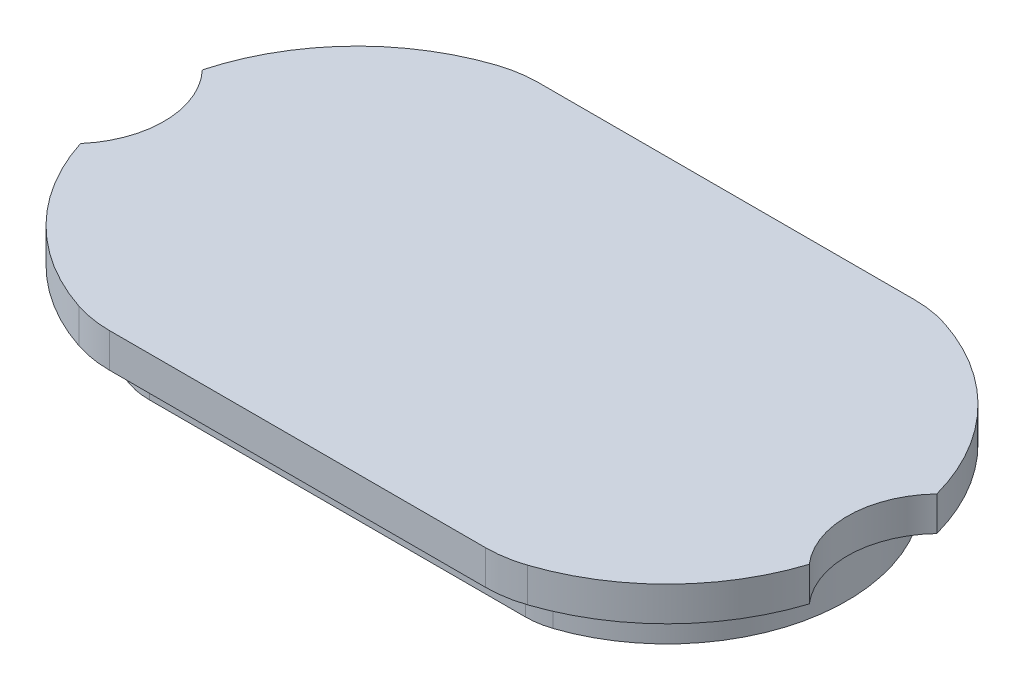
SolidWorks part; units mm, degrees
ref_plane "Front Plane" through (0, 0, 0) normal (0, 0, 1) x (1, 0, 0)
ref_plane "Top Plane" through (0, 0, 0) normal (0, 1, 0) x (1, 0, 0)
ref_plane "Right Plane" through (0, 0, 0) normal (1, 0, 0) x (0, 0, -1)
sketch "Sketch1" plane through (0, 0, 0) normal (0, 1, 0) x (1, 0, 0)
  line L4 (34.5405, 38.6091) -> (-36.4595, 38.6091)
  line L6 (34.5405, -36.3909) -> (-36.4595, -36.3909)
  arc A0 (-36.4595, 38.6091) -> (-36.4595, -36.3909) centre (-28.022, 1.1091) ccw
  arc A1 (34.5405, 38.6091) -> (34.5405, -36.3909) centre (26.103, 1.1091) cw
  point P11 (0.5405, 0.9091)
extrude "Boss-Extrude1" add sketch "Sketch1" along normal blind 6
fillet "Fillet1" radius 20 4 edges at (34.5405, 3, 36.3909) (34.5405, 3, -38.6091) (-36.4595, 3, -38.6091) (-36.4595, 3, 36.3909)
sketch "Sketch3" plane through (0, 0, 0) normal (0, -1, 0) x (1, 0, 0)
  line L4 (31.9074, 29.3909) -> (-33.8264, 29.3909)
  line L5 (-33.8264, -31.6091) -> (31.9074, -31.6091)
  line L6 (31.9074, 29.3909) -> (-33.8264, 29.3909)
  line L7 (-33.8264, -31.6091) -> (31.9074, -31.6091)
  arc A4 (36.0001, -30.9481) -> (36.0001, 28.7299) centre (26.103, -1.1091) ccw
  arc A5 (36.0001, -30.9481) -> (36.0001, 28.7299) centre (26.103, -1.1091) ccw
  arc A6 (-37.919, 28.7299) -> (-37.919, -30.9481) centre (-28.022, -1.1091) ccw
  arc A7 (-37.919, 28.7299) -> (-37.919, -30.9481) centre (-28.022, -1.1091) ccw
  arc A10 (-37.919, -30.9481) -> (-33.8264, -31.6091) centre (-33.8264, -18.6091) ccw
  arc A11 (-37.919, -30.9481) -> (-33.8264, -31.6091) centre (-33.8264, -18.6091) ccw
  arc A12 (36.0001, 28.7299) -> (31.9074, 29.3909) centre (31.9074, 16.3909) ccw
  arc A13 (36.0001, 28.7299) -> (31.9074, 29.3909) centre (31.9074, 16.3909) ccw
  arc A14 (31.9074, -31.6091) -> (36.0001, -30.9481) centre (31.9074, -18.6091) ccw
  arc A15 (-33.8264, 29.3909) -> (-37.919, 28.7299) centre (-33.8264, 16.3909) ccw
  arc A16 (31.9074, -31.6091) -> (36.0001, -30.9481) centre (31.9074, -18.6091) ccw
  arc A17 (-33.8264, 29.3909) -> (-37.919, 28.7299) centre (-33.8264, 16.3909) ccw
  dimension "D1" = 7
ref_plane "Plane1" through (31.9074, 0, -31.6091) normal (1, 0, 0) x (0, 0, -1)
sketch "Sketch4" plane through (31.9074, 0, -31.6091) normal (1, 0, 0) x (0, 0, -1)
  line L1 (0, 0) -> (-3, 0)
  line L2 (0, 0) -> (0, -8)
  line L3 (0, -8) -> (-3, -8)
  line L4 (-3, 0) -> (-3, -8)
sweep "Sweep1" add profiles "Sketch4" path "Sketch3"
sketch "Sketch6" plane through (0, 0, 0) normal (0, 1, 0) x (1, 0, 0)
  circle A0 centre (75, 0) radius 16.2457
  circle A1 centre (-76.919, 0) radius 16.2457
extrude "Cut-Extrude1" cut sketch "Sketch6" along normal blind 10
